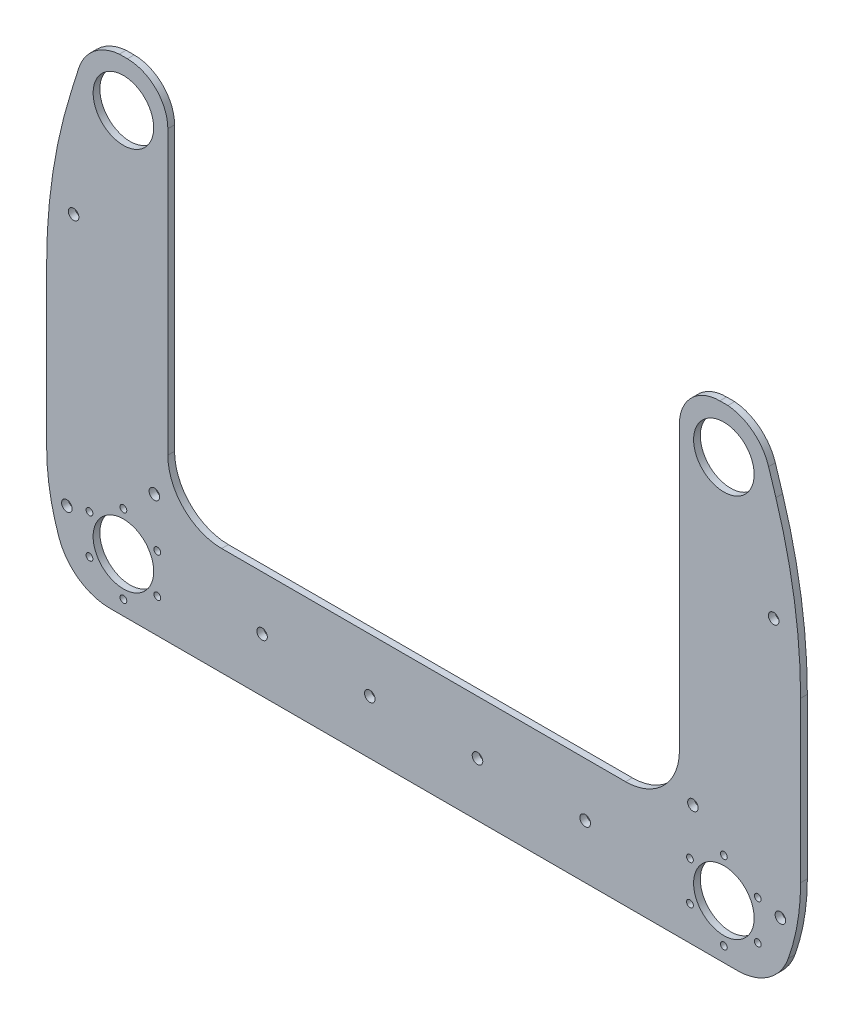
SolidWorks part; units mm, degrees
material "6061 Alloy"
ref_plane "Front Plane" through (0, 0, 0) normal (0, 0, 1) x (1, 0, 0)
ref_plane "Top Plane" through (0, 0, 0) normal (0, 1, 0) x (1, 0, 0)
ref_plane "Right Plane" through (0, 0, 0) normal (1, 0, 0) x (0, 0, -1)
sketch "Sketch1" plane through (0, 0, 0) normal (0, 0, 1) x (1, 0, 0)
  line L5 (120.65, -152.4) -> (120.65, -6.35)
  line L6 (127, 0) -> (171.45, 0) construction
  line L7 (177.8, -6.35) -> (177.8, -222.25)
  line L10 (0, -206.2199) -> (0, -63.6275) construction
  line L11 (-54.9244, 0) -> (300.6756, 0) construction
  line L13 (12.7, -177.8) -> (95.25, -177.8)
  line L14 (12.7, -228.6) -> (171.45, -228.6)
  line L15 (141.605, -25.4) -> (141.605, -84.2822) construction
  line L16 (141.605, -22.0269) -> (141.605, -123.6269) construction
  line L17 (-141.605, -22.0269) -> (-141.605, -203.2) construction
  line L18 (-141.605, -22.0269) -> (-141.605, -123.6269) construction
  line L19 (-141.605, -19.0512) -> (-141.605, -77.9333) construction
  line L20 (141.605, -22.0269) -> (141.605, -203.2) construction
  line L22 (-120.65, -152.4) -> (-120.65, -6.35)
  line L23 (-12.7, -177.8) -> (-95.25, -177.8)
  line L24 (-12.7, -228.6) -> (-171.45, -228.6)
  line L25 (-177.8, -6.35) -> (-177.8, -222.25)
  line L26 (-12.7, -177.8) -> (12.7, -177.8)
  line L27 (-12.7, -228.6) -> (12.7, -228.6)
  line L28 (-177.8, -6.35) -> (-177.8, 6.35)
  line L29 (-165.1, 19.05) -> (-133.35, 19.05)
  line L30 (-120.65, 6.35) -> (-120.65, -6.35)
  line L31 (120.65, 6.35) -> (120.65, -6.35)
  line L32 (177.8, -6.35) -> (177.8, 6.35)
  line L33 (165.1, 19.05) -> (133.35, 19.05)
  arc A0 (95.25, -177.8) -> (120.65, -152.4) centre (95.25, -152.4) ccw
  arc A4 (120.65, -6.35) -> (127, 0) centre (127, -6.35) cw construction
  circle A8 centre (141.605, -22.0269) radius 14.2875
  circle A9 centre (141.605, -22.0269) radius 38.1 construction
  arc A10 (177.8, -6.35) -> (171.45, 0) centre (171.45, -6.35) ccw construction
  arc A11 (171.45, -228.6) -> (177.8, -222.25) centre (171.45, -222.25) ccw
  arc A14 (141.605, -79.1769) -> (120.9214, -75.3027) centre (141.605, -22.0269) ccw construction
  arc A15 (-141.605, -79.1769) -> (-120.9214, -75.3027) centre (-141.605, -22.0269) cw construction
  circle A16 centre (-141.605, -22.0269) radius 38.1 construction
  circle A17 centre (-141.605, -22.0269) radius 14.2875
  arc A19 (-95.25, -177.8) -> (-120.65, -152.4) centre (-95.25, -152.4) cw
  circle A20 centre (141.605, -123.6269) radius 38.1 construction
  circle A21 centre (-141.605, -123.6269) radius 38.1 construction
  arc A23 (-171.45, -228.6) -> (-177.8, -222.25) centre (-171.45, -222.25) cw
  circle A24 centre (-141.605, -203.2) radius 14.2875
  circle A25 centre (-141.605, -184.7248) radius 1.6002
  circle A26 centre (-125.604, -193.963) radius 1.6002
  circle A27 centre (-125.604, -212.4393) radius 1.6002
  circle A28 centre (-141.605, -221.6775) radius 1.6002
  circle A29 centre (-157.606, -212.4393) radius 1.6002
  circle A30 centre (-157.606, -193.963) radius 1.6002
  circle A31 centre (157.606, -212.4393) radius 1.6002
  circle A32 centre (157.606, -193.963) radius 1.6002
  circle A33 centre (141.605, -184.7248) radius 1.6002
  circle A34 centre (125.604, -193.963) radius 1.6002
  circle A35 centre (125.604, -212.4393) radius 1.6002
  circle A36 centre (141.605, -221.6775) radius 1.6002
  circle A37 centre (141.605, -203.2) radius 14.2875
  circle A39 centre (-76.2, -203.2) radius 2.4892
  circle A40 centre (76.2, -203.2) radius 2.4892
  circle A42 centre (-25.4, -203.2) radius 2.4892
  circle A43 centre (-127, -171.45) radius 2.4892
  arc A44 (-133.35, 19.05) -> (-120.65, 6.35) centre (-133.35, 6.35) cw
  arc A45 (-177.8, 6.35) -> (-165.1, 19.05) centre (-165.1, 6.35) cw
  arc A46 (133.35, 19.05) -> (120.65, 6.35) centre (133.35, 6.35) ccw
  arc A47 (177.8, 6.35) -> (165.1, 19.05) centre (165.1, 6.35) ccw
  circle A50 centre (-149.225, 6.35) radius 2.4892
  circle A51 centre (127, -171.45) radius 2.4892
  circle A53 centre (149.225, 6.35) radius 2.4892
  circle A54 centre (-168.275, -196.85) radius 2.4892
  circle A56 centre (168.275, -196.85) radius 2.4892
  circle A58 centre (-165.1, -76.2) radius 2.4892
  circle A59 centre (165.1, -76.2) radius 2.4892
  circle A60 centre (25.4, -203.2) radius 2.4892
  point P2 (177.8, -44.45)
  point P18 (177.8, 0)
  point P23 (177.8, -228.6)
  point P24 (177.8, -228.6)
  point P31 (177.8, 0)
  point P48 (-177.8, 0)
  point P49 (-177.8, -228.6)
  point P51 (-177.8, -44.45)
  point P78 (-141.605, -203.2012)
  dimension "D6" = 25.4
  dimension "D7" = 6.35
  dimension "D8" = 6.35
  dimension "D9" = 177.8
  dimension "D10" = 28.575
  dimension "D12" = 76.2
  dimension "D13" = 57.15
  dimension "D15" = 28.575
  dimension "D18" = 76.2
  dimension "D21" = 3.2004
  dimension "D29" = 9.525
  dimension "D32" = 4.9784
  dimension "D35" = 4.9784
  dimension "D37" = 4.9784
  dimension "D40" = 12.7
  dimension "D43" = 4.9784
  dimension "D45" = 12.7
  dimension "D30" = 4.9784
  dimension "D41" = 4.9784
  dimension "D2" = 120.65
  dimension "D3" = 177.8
  dimension "D4" = 228.6
  dimension "D5" = 177.8
  dimension "D11" = 20.955
  dimension "`" = 22.0269
  dimension "D14" = 57.15
  dimension "D16" = 184.15
  dimension "D17" = 101.6
  dimension "D19" = 25.4
  dimension "D20" = 101.6
  dimension "D22" = 0
  dimension "D23" = 18.4752
  dimension "D25" = 6.9225
  dimension "D26" = 31.75
  dimension "D27" = 25.4
  dimension "D28" = 25.4
  dimension "D31" = 95.25
  dimension "D33" = 12.7
  dimension "D34" = 25.4
  dimension "D38" = 57.15
  dimension "D39" = 19.05
  dimension "D42" = 6.35
  dimension "D44" = 28.575
  dimension "D46" = 25.4
  dimension "D24" = 6
extrude "Boss-Extrude3" add sketch "Sketch1" along normal blind 3.175
sketch "Sketch2" plane through (0, 0, 3.175) normal (0, 0, 1) x (1, 0, 0)
  line L0 (-133.35, 19.05) -> (-165.1, 19.05) construction
  line L1 (-177.8, 19.05) -> (177.8, 19.05)
  line L2 (-177.8, 19.05) -> (-177.8, 0)
  line L3 (-177.8, 0) -> (177.8, 0)
  line L4 (177.8, 19.05) -> (177.8, 0)
  line L5 (-177.8, 6.35) -> (-177.8, -222.25) construction
  line L6 (177.8, -222.25) -> (177.8, 6.35) construction
  dimension "D1" = 19.05
extrude "Cut-Extrude1" cut sketch "Sketch2" against normal through all
fillet "Fillet1" radius 19.05 4 edges at (177.8, 0, 1.5875) (120.65, 0, 1.5875) (-120.65, 0, 1.5875) (-177.8, 0, 1.5875)
sketch "Sketch3" plane through (0, 0, 3.175) normal (0, 0, 1) x (1, 0, 0)
  line L2 (-177.8, -19.05) -> (-177.8, -222.25) construction
  line L3 (-158.75, 0) -> (-139.7, 0) construction
  line L4 (-177.8, -63.5) -> (-177.8, 0)
  line L5 (-177.8, 0) -> (-139.7, 0)
  line L6 (-162.6988, -15.4039) -> (-177.8, -63.5)
  circle A0 centre (-141.605, -22.0269) radius 22.1091 construction
  arc A1 (-120.65, -19.05) -> (-139.7, 0) centre (-139.7, -19.05) ccw construction
  arc A2 (-120.65, -19.05) -> (-139.7, 0) centre (-139.7, -19.05) ccw construction
  arc A3 (-139.7, 0) -> (-162.6988, -15.4039) centre (-141.605, -22.0269) ccw
  dimension "D1" = 63.5
extrude "Cut-Extrude2" cut sketch "Sketch3" against normal through all
ref_plane "Plane1" through (0, 0, 0) normal (1, 0, 0) x (0, 0, -1)
mirror "Mirror1" about plane through (0, 0, 0) normal (1, 0, 0) of "Cut-Extrude2"
fillet "Fillet2" radius 254 1 edges at (-177.8, -63.5, 1.5875)
fillet "Fillet3" radius 254 1 edges at (177.8, -63.5, 1.5875)
sketch "Sketch4" plane through (0, 0, 3.175) normal (0, 0, 1) x (1, 0, 0)
  line L0 (-177.8, -102.4383) -> (-177.8, -222.25) construction
  line L4 (-171.45, -228.6) -> (171.45, -228.6) construction
  line L5 (-177.8, -177.8) -> (-177.8, -228.6)
  line L6 (-177.8, -228.6) -> (-164.1882, -228.6)
  line L7 (0, -206.4784) -> (0, -94.7413) construction
  line L8 (177.8, -228.6) -> (164.1882, -228.6)
  line L9 (177.8, -177.8) -> (177.8, -228.6)
  circle A0 centre (-76.2, -177.8) radius 101.6 construction
  arc A2 (-164.1882, -228.6) -> (-177.8, -177.8) centre (-76.2, -177.8) cw
  arc A3 (164.1882, -228.6) -> (177.8, -177.8) centre (76.2, -177.8) ccw
  point P11 (-170.9941, -228.6)
  point P14 (170.9941, -228.6)
  line M38 (177.8, -222.25) -> (177.8, -102.4383)
  line M54 (-177.8, -102.4383) -> (-177.8, -222.25)
  arc M55 (-177.8, -222.25) -> (-171.45, -228.6) centre (-171.45, -222.25) ccw
  line M56 (-171.45, -228.6) -> (171.45, -228.6)
  arc M57 (171.45, -228.6) -> (177.8, -222.25) centre (171.45, -222.25) ccw
  dimension "D1" = 203.2
  dimension "D2" = 50.8
extrude "Cut-Extrude3" cut sketch "Sketch4" against normal through all contours A2 M56 M54 M55 | A3 M56 M57 M38
fillet "Fillet4" radius 25.4 2 edges at (164.1882, -228.6, 1.5875) (-164.1882, -228.6, 1.5875)
